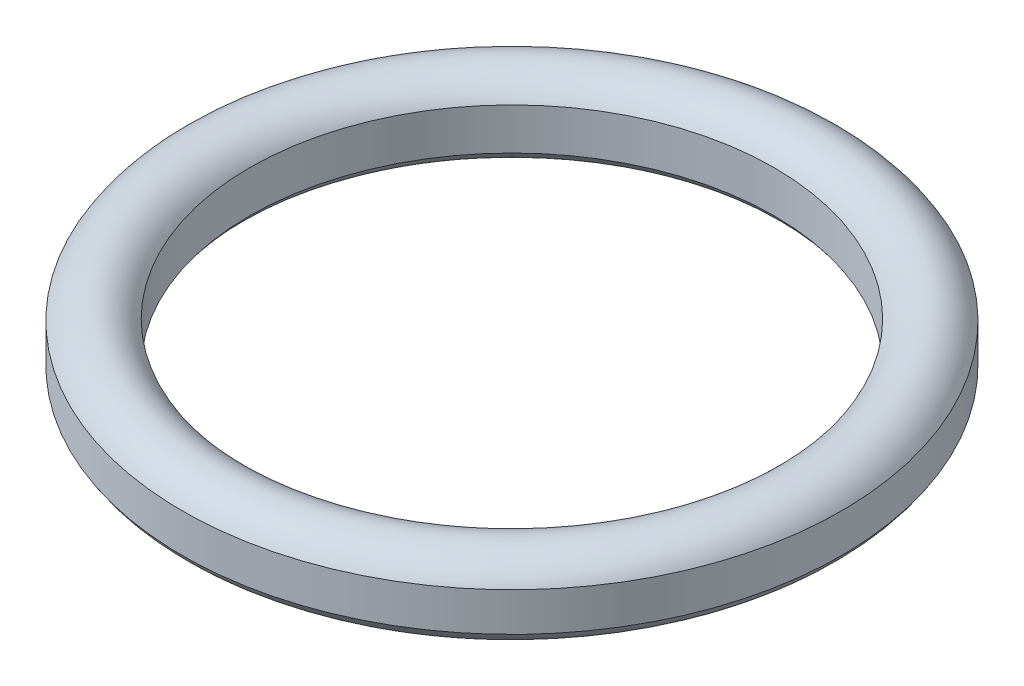
SolidWorks part; units mm, degrees
material "NBR"
ref_plane "Piano frontale" through (0, 0, 0) normal (0, 0, 1) x (1, 0, 0)
ref_plane "Piano superiore" through (0, 0, 0) normal (0, 1, 0) x (1, 0, 0)
ref_plane "Piano destro" through (0, 0, 0) normal (1, 0, 0) x (0, 0, -1)
sketch "Schizzo1" plane through (0, 0, 0) normal (0, 0, 1) x (1, 0, 0)
  line L0 (-9.86, 0) -> (0, 0) construction
  line L1 (0, 0) -> (0, 8.7785) construction
  line L2 (-8.75, -0.6957) -> (-8.75, 0.6957)
  line L3 (-11, -0.6454) -> (-11, 0.6454)
  circle A0 centre (-9.86, 0) radius 1.31
  dimension "D2" = 2.62
  dimension "D1" = 19.72
  dimension "D3" = 22
  dimension "D4" = 17.5
revolve "Rivoluzione1" add sketch "Schizzo1" angle 360 about L1
